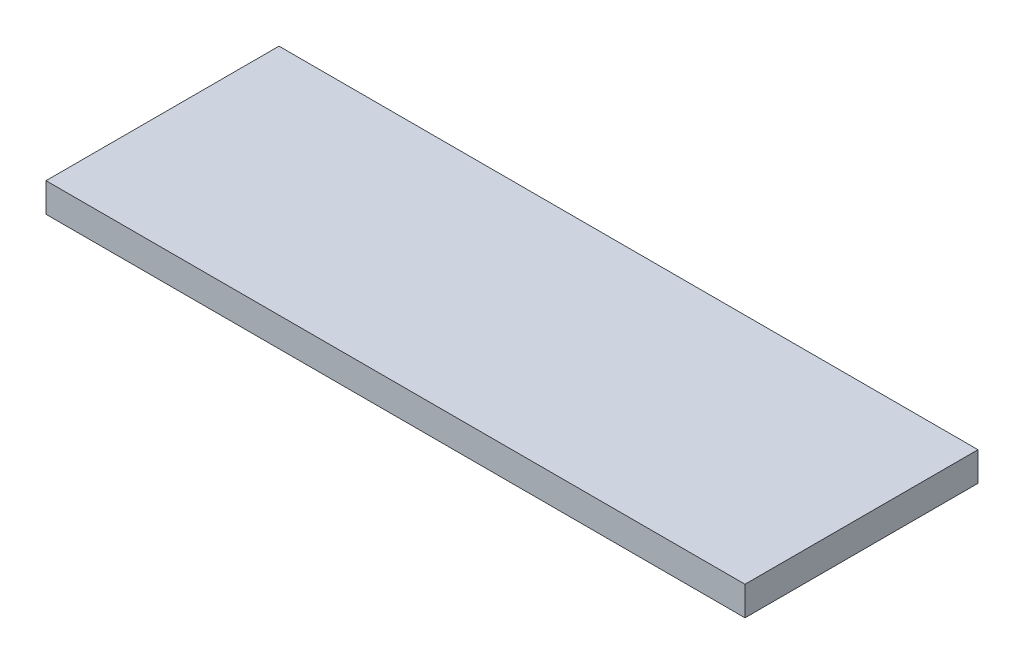
SolidWorks part; units mm, degrees
material "ASTM A36 Steel"
ref_plane "Front Plane" through (0, 0, 0) normal (0, 0, 1) x (1, 0, 0)
ref_plane "Top Plane" through (0, 0, 0) normal (0, 1, 0) x (1, 0, 0)
ref_plane "Right Plane" through (0, 0, 0) normal (1, 0, 0) x (0, 0, -1)
sketch "Sketch1" plane through (0, 0, 0) normal (0, 1, 0) x (1, 0, 0)
  line L1 (-114.3, -38.1) -> (114.3, -38.1)
  line L2 (-114.3, -38.1) -> (-114.3, 38.1)
  line L3 (-114.3, 38.1) -> (114.3, 38.1)
  line L4 (114.3, -38.1) -> (114.3, 38.1)
  line L5 (-114.3, -38.1) -> (114.3, 38.1) construction
  line L6 (-114.3, 38.1) -> (114.3, -38.1) construction
  line L7 (-114.3, 0) -> (114.3, 0) construction
  point P0 (0, 0)
  dimension "D1" = 228.6
  dimension "D2" = 76.2
extrude "Boss-Extrude1" add sketch "Sketch1" along normal blind 9.525
